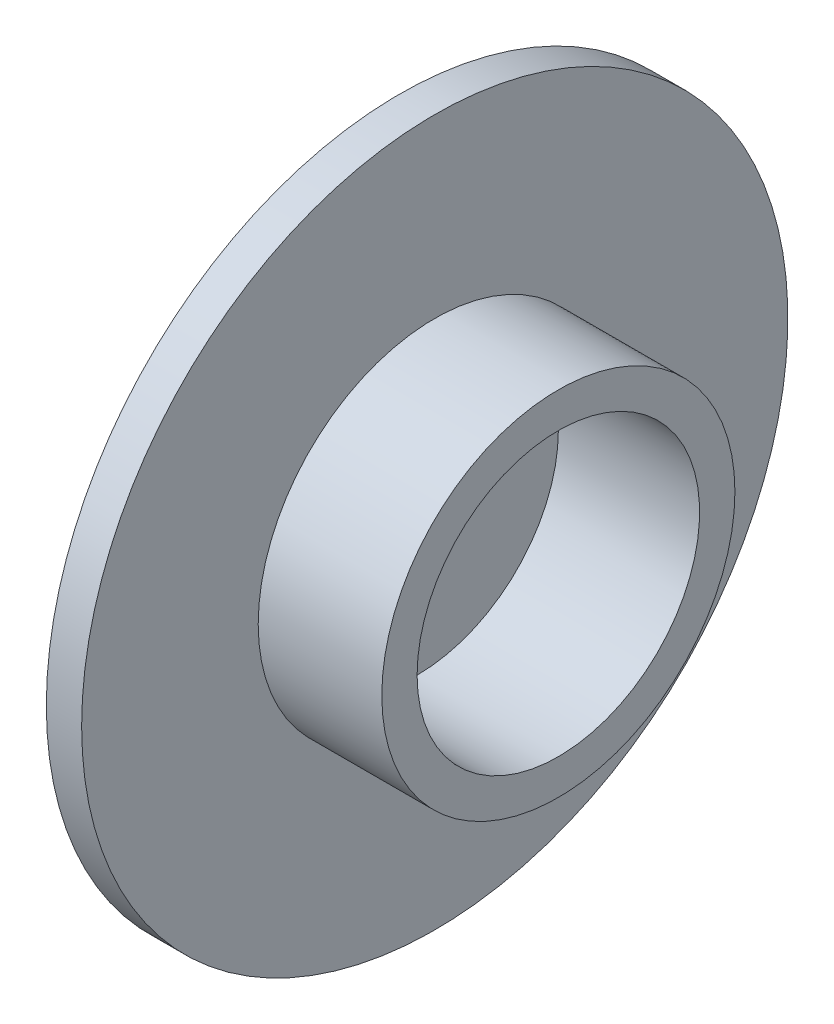
SolidWorks part; units mm, degrees
ref_plane "Front Plane" through (0, 0, 0) normal (0, 0, 1) x (1, 0, 0)
ref_plane "Top Plane" through (0, 0, 0) normal (0, 1, 0) x (1, 0, 0)
ref_plane "Right Plane" through (0, 0, 0) normal (1, 0, 0) x (0, 0, -1)
sketch "Sketch1" plane through (0, 0, 0) normal (0, 0, 1) x (1, 0, 0)
  line L0 (0.9059, 10.4184) -> (2.9059, 10.4184)
  line L1 (2.9059, 10.4184) -> (2.9059, 0.4184)
  line L2 (2.9059, 0.4184) -> (9.9059, 0.4184)
  line L3 (0.9059, 8.4184) -> (0.9059, 10.4184)
  line L4 (0.9059, 8.4184) -> (0.9059, -1.5816)
  line L5 (0.9059, -1.5816) -> (9.9059, -1.5816)
  line L6 (0.9059, 8.4184) -> (0.9059, 8.4184) construction
  line L7 (9.9059, -1.5816) -> (9.9059, 0.4184)
  line L8 (0.9059, -9.5816) -> (29.0464, -9.5816) construction
  dimension "D1" = 2
  dimension "D2" = 10
  dimension "D3" = 7
  dimension "D5" = 8
  dimension "D4" = 2
revolve "Revolve1" add sketch "Sketch1" angle 360 about L8
sketch "Sketch2" plane through (9.9059, 0, 0) normal (1, 0, 0) x (0, 0, -1)
  circle A0 centre (0, -9.5816) radius 10
extrude "Boss-Extrude1" add sketch "Sketch2" along normal blind 1 from surface
